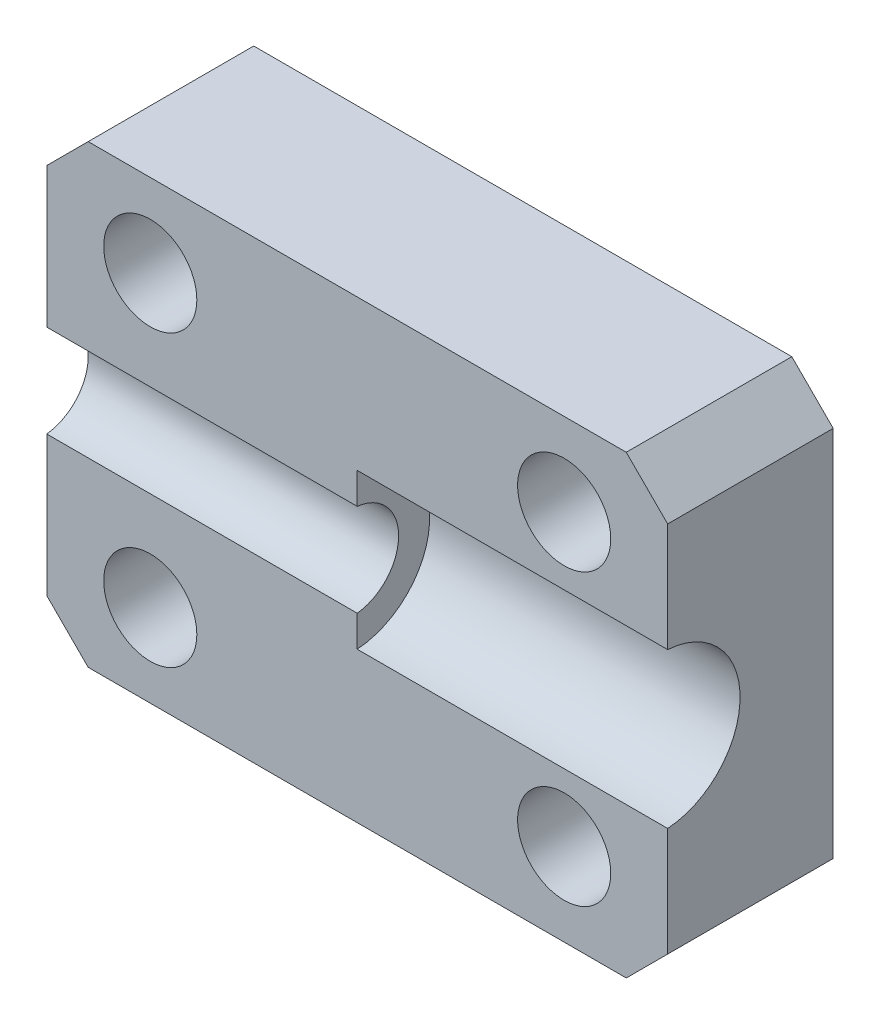
SolidWorks part; units mm, degrees
material "Printed PLA"
ref_plane "Front Plane" through (0, 0, 0) normal (0, 0, 1) x (1, 0, 0)
ref_plane "Top Plane" through (0, 0, 0) normal (0, 1, 0) x (1, 0, 0)
ref_plane "Right Plane" through (0, 0, 0) normal (1, 0, 0) x (0, 0, -1)
sketch "Sketch2" plane through (0, 0, 0) normal (0, 0, 1) x (1, 0, 0)
  line L0 (-15, 11) -> (15, -11) construction
  line L1 (-13, 11) -> (13, 11)
  line L2 (-15, 9) -> (-15, -9)
  line L3 (-13, -11) -> (13, -11)
  line L4 (15, 9) -> (15, -9)
  line L5 (10, -7) -> (-10, -7) construction
  line L6 (-10, -7) -> (-10, 7) construction
  line L7 (-10, 7) -> (10, 7) construction
  line L8 (10, 7) -> (10, -7) construction
  line L9 (10, -7) -> (-10, 7) construction
  line L10 (-15, 9) -> (-13, 11)
  line L11 (13, 11) -> (15, 9)
  line L12 (13, -11) -> (15, -9)
  line L13 (-15, -9) -> (-13, -11)
  circle A0 centre (-10, 7) radius 2.25
  circle A1 centre (-10, -7) radius 2.25
  circle A2 centre (10, 7) radius 2.25
  circle A3 centre (10, -7) radius 2.25
  point P2 (-15, -11)
  point P3 (15, 11)
  dimension "D5" = 4.5
  dimension "D1" = 30
  dimension "D2" = 22
  dimension "D3" = 20
  dimension "D4" = 14
extrude "Boss-Extrude1" add sketch "Sketch2" along normal blind 8
sketch "Sketch3" plane through (15, 0, 0) normal (1, 0, 0) x (0, 0, -1)
  line L0 (-8, -9) -> (-8, 9) construction
  line L1 (-8.25, 0) -> (0, 0) construction
  circle A0 centre (-8.25, 0) radius 2.25
  dimension "D1" = 4.5
  dimension "D2" = 0.25
extrude "Cut-Extrude1" cut sketch "Sketch3" against normal up to next
sketch "Sketch4" plane through (15, 0, 0) normal (1, 0, 0) x (0, 0, -1)
  circle A0 centre (-8.25, 0) radius 3.75
  dimension "D1" = 7.5
extrude "Cut-Extrude2" cut sketch "Sketch4" against normal blind 15
